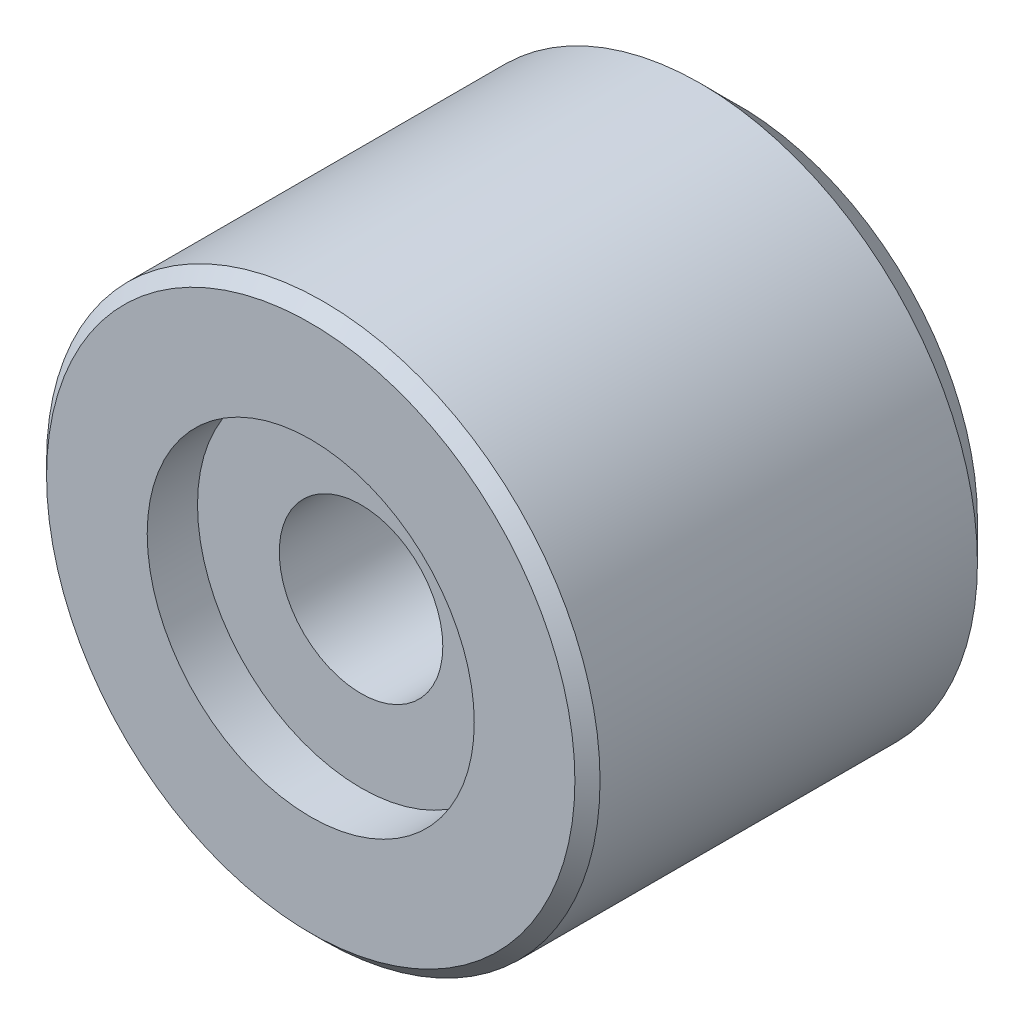
SolidWorks part; units mm, degrees
ref_plane "Front Plane" through (0, 0, 0) normal (0, 0, 1) x (1, 0, 0)
ref_plane "Top Plane" through (0, 0, 0) normal (0, 1, 0) x (1, 0, 0)
ref_plane "Right Plane" through (0, 0, 0) normal (1, 0, 0) x (0, 0, -1)
sketch "Sketch1" plane through (0, 0, 0) normal (0, 0, 1) x (1, 0, 0)
  circle A0 centre (0, 0) radius 11
  dimension "D1" = 22
extrude "Boss-Extrude1" add sketch "Sketch1" along normal blind 17 contours A0
sketch "Sketch2" plane through (0, 0, 17) normal (0, 0, 1) x (1, 0, 0)
  line L1 (1.6, 2.8289) -> (1.6, -2.8289)
  arc A0 (1.6, 2.8289) -> (1.6, -2.8289) centre (0, 0) ccw
  point P1 (-3.25, 0)
  dimension "D2" = 3.25
  dimension "D1" = 4.85
extrude "Cut-Extrude1" cut sketch "Sketch2" against normal blind 12.5
sketch "Sketch3" plane through (0, 0, 17) normal (0, 0, 1) x (1, 0, 0)
  circle A0 centre (0, 0) radius 6.5
extrude "Cut-Extrude2" cut sketch "Sketch3" against normal blind 2
sketch "Sketch4" plane through (0, 0, 17) normal (0, 0, 1) x (1, 0, 0)
  circle A0 centre (0, 0) radius 3.25
  arc A1 (1.6, 2.8289) -> (1.6, -2.8289) centre (0, 0) ccw construction
extrude "Cut-Extrude3" cut sketch "Sketch4" against normal blind 4.5
chamfer "Chamfer1" distance 1.5 angle 45 1 edges at (11, 0, 0)
chamfer "Chamfer2" distance 0.5 angle 45 1 edges at (11, 0, 17)
equation "\"D2@Sketch2\"=3+.25"
equation "\"D1@Sketch2\"=4.45+.4"
